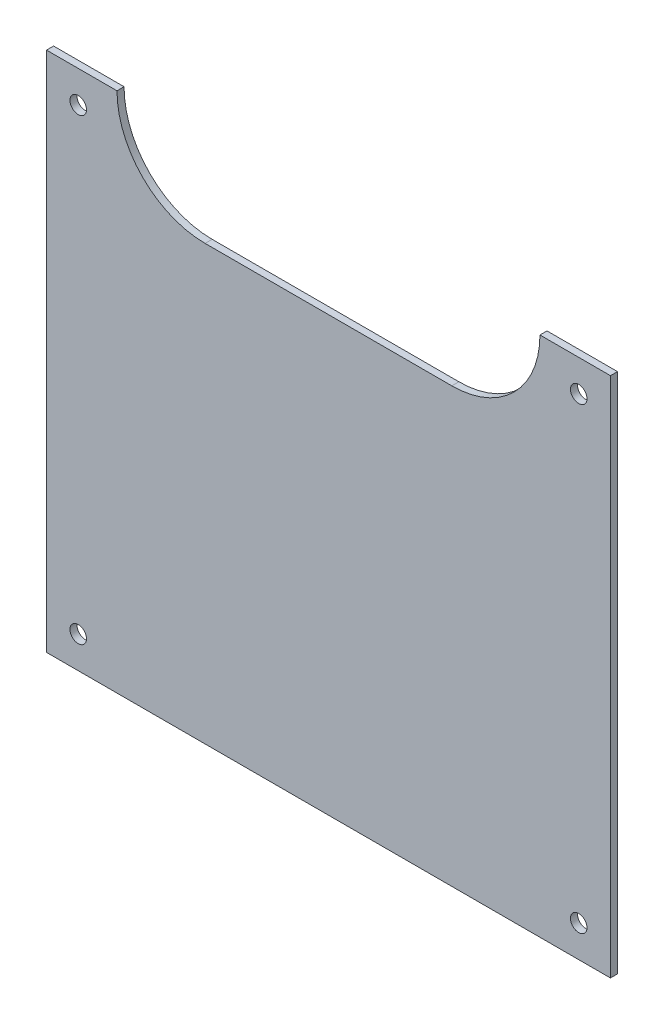
SolidWorks part; units mm, degrees
ref_plane "Ebene vorne" through (0, 0, 0) normal (0, 0, 1) x (1, 0, 0)
ref_plane "Ebene oben" through (0, 0, 0) normal (0, 1, 0) x (1, 0, 0)
ref_plane "Ebene rechts" through (0, 0, 0) normal (1, 0, 0) x (0, 0, -1)
sketch "Skizze1" plane through (0, 0, 0) normal (0, 0, 1) x (1, 0, 0)
  line L0 (-35, 49) -> (35, 49)
  line L1 (80, -74) -> (-80, -74)
  line L2 (80, -74) -> (80, 74)
  line L3 (80, 74) -> (60, 74)
  line L4 (-80, -74) -> (-80, 74)
  line L5 (80, -74) -> (-80, 74) construction
  line L6 (80, 74) -> (-80, -74) construction
  line L7 (-60, 74) -> (-80, 74)
  arc A0 (-60, 74) -> (-35, 49) centre (-35, 74) ccw
  arc A1 (35, 49) -> (60, 74) centre (35, 74) ccw
  point P0 (0, 0)
  dimension "D3" = 50
  dimension "D4" = 50
  dimension "D1" = 148
  dimension "D2" = 160
  dimension "D5" = 45
  dimension "D6" = 45
extrude "Aufsatz-Linear austragen1" add sketch "Skizze1" along normal blind 2
sketch "Skizze3" plane through (0, 0, 2) normal (0, 0, 1) x (1, 0, 0)
  line L1 (-71, 65) -> (-71, -65) construction
  line L2 (-60, 65) -> (-80, 65)
  line L3 (-60, 65) -> (-71, 65) construction
  line L14 (71, -65) -> (71, 65)
  line L15 (-71, -65) -> (71, -65)
  line L16 (-71, 74) -> (-71, -65)
  line L17 (71, 65) -> (60, 65)
  line L18 (71, -65) -> (71, 65) construction
  line L19 (-71, -65) -> (71, -65) construction
  line L20 (-71, 74) -> (-71, 71.65) construction
  line L21 (71, 65) -> (60, 65) construction
  circle A0 centre (71, 65) radius 2.35
  circle A2 centre (-71, -65) radius 2.35
  circle A3 centre (71, -65) radius 2.35
  circle A4 centre (-71, 65) radius 2.35
  dimension "D2" = 4.7
  dimension "D3" = 9
  dimension "D1" = 9
extrude "Schnitt-Linear austragen1" cut sketch "Skizze3" against normal through all
equation "\"D6@Skizze1\"=\"D5@Skizze1\""
